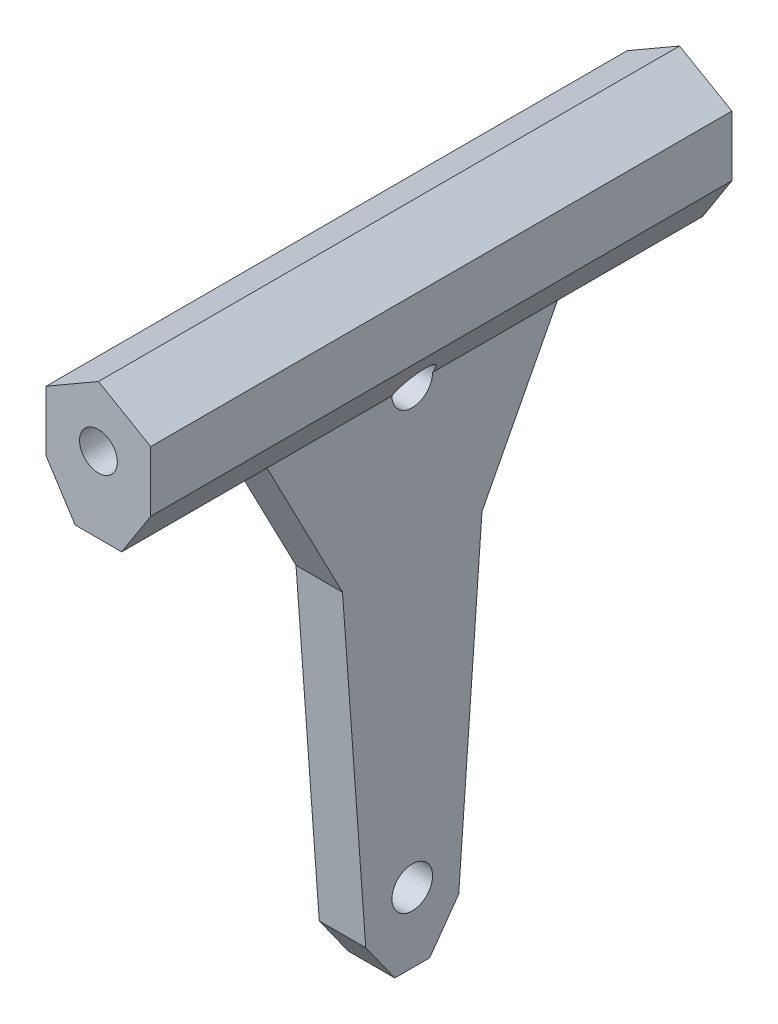
SolidWorks part; units mm, degrees
ref_plane "Front Plane" through (0, 0, 0) normal (0, 0, 1) x (1, 0, 0)
ref_plane "Top Plane" through (0, 0, 0) normal (0, 1, 0) x (1, 0, 0)
ref_plane "Right Plane" through (0, 0, 0) normal (1, 0, 0) x (0, 0, -1)
sketch "草圖1" plane through (0, 0, 0) normal (0, 0, 1) x (1, 0, 0)
  line L1 (-9, 5.1962) -> (-9, -5.1962)
  line L4 (9, -5.1962) -> (9, 5.1962)
  line L5 (9, 5.1962) -> (0, 10.3923)
  line L6 (0, 10.3923) -> (-9, 5.1962)
  line L8 (-9, -5.1962) -> (-4, -13)
  line L9 (-9, -5.1962) -> (-4.5, -7.7942) [skipped]
  line L10 (4.5, -7.7942) -> (9, -5.1962) [skipped]
  line L11 (-4, -13) -> (-4, -100)
  line L12 (-4, -100) -> (4, -100)
  line L13 (4, -100) -> (4, -13)
  line L14 (4, -13) -> (9, -5.1962)
  arc A0 (9, 0) -> (-9, 0) centre (0, 0) ccw construction
  circle A1 centre (0, 0) radius 3.25
  point P8 (0, 0)
  point P19 (0, 0)
  point P20 (0, 0)
  point P21 (0, 0)
  point P22 (0, 0)
  point P24 (0, 0)
  dimension "D1" = 18
  dimension "D2" = 6.5
  dimension "D3" = 5.1962
  dimension "D4" = 13
  dimension "D5" = 4
  dimension "D6" = 4
  dimension "D7" = 100
extrude "填料-伸長1" add sketch "草圖1" along normal blind 100
sketch "草圖2" plane through (-4, 0, 0) normal (-1, 0, 0) x (0, 0, 1)
  line L0 (100, -13) -> (0, -13) construction
  line L2 (0, -13) -> (25, -13)
  line L3 (25, -13) -> (38, -38)
  line L4 (38, -38) -> (42, -93)
  line L5 (42, -93) -> (47, -100)
  line L6 (100, -100) -> (0, -100) construction
  line L7 (47, -100) -> (53, -100)
  line L8 (53, -100) -> (58, -93)
  line L9 (58, -93) -> (62, -38)
  line L10 (62, -38) -> (75, -13)
  line L11 (75, -13) -> (100, -13)
  line L12 (100, -13) -> (100, -100)
  line L13 (100, -100) -> (75.2334, -107.4548)
  line L14 (75.2334, -107.4548) -> (14.0964, -107.4548)
  line L15 (14.0964, -107.4548) -> (0, -100)
  line L16 (0, -100) -> (0, -13)
  circle A0 centre (50, -13) radius 3.5
  circle A1 centre (50, -88) radius 3.5
  point P6 (0, 0)
  point P27 (0, 0)
  line M17 (0, -13) -> (0, -100)
  line M18 (0, -100) -> (100, -100)
  line M19 (100, -100) -> (100, -13)
  line M20 (100, -13) -> (0, -13)
  dimension "D2" = 7
  dimension "D1" = 75
  dimension "D3" = 25
  dimension "D4" = 25
  dimension "D5" = 25
  dimension "D6" = 12
  dimension "D7" = 12
  dimension "D8" = 8
  dimension "D9" = 8
  dimension "D10" = 80
  dimension "D11" = 3
  dimension "D12" = 3
extrude "除料-伸長1" cut sketch "草圖2" against normal through all and the other way through all contours L5 L4 L3 M20 M17 M18 | L10 L9 L8 M18 M19 M20 | L15 L14 L13 M18 | A0 M20 | A1
